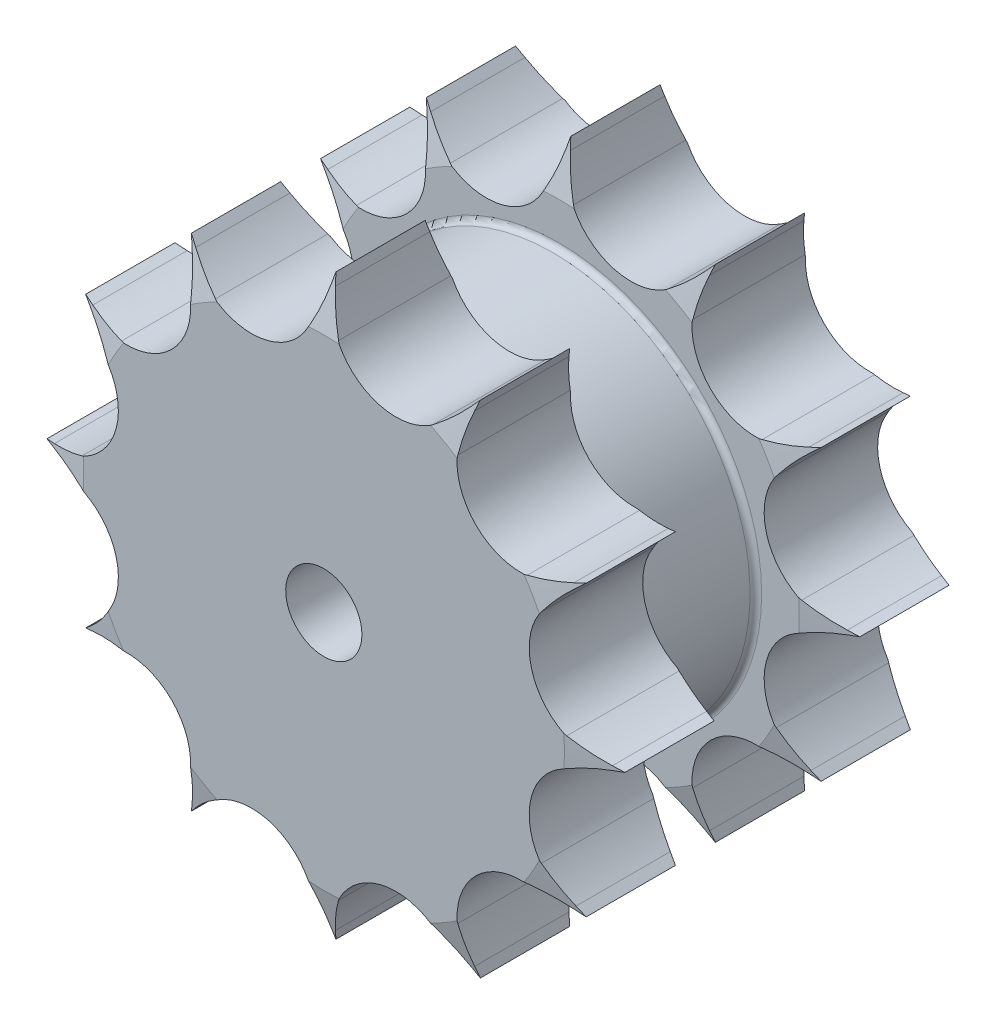
SolidWorks part; units mm, degrees
ref_plane "Front Plane" through (0, 0, 0) normal (0, 0, 1) x (1, 0, 0)
ref_plane "Top Plane" through (0, 0, 0) normal (0, 1, 0) x (1, 0, 0)
ref_plane "Right Plane" through (0, 0, 0) normal (1, 0, 0) x (0, 0, -1)
sketch "Sketch0" plane through (0, 0, 0) normal (0, 0, 1) x (1, 0, 0)
  line L0 (9, -33.5885) -> (0, 0) construction
  line L1 (0, 0) -> (24.5885, -24.5885) construction
  line L2 (0, 0) -> (-9, -33.5885) construction
  line L3 (9, -33.5885) -> (24.5885, -24.5885) construction
  line L4 (9, -33.5885) -> (-9, -33.5885) construction
  line L5 (18.2038, -31.414) -> (17.1631, -30.2446)
  line L6 (9, -33.5885) -> (0, -36) construction
  line L7 (-0.0579, -36.3072) -> (0.2586, -34.7741)
  line L8 (0, -33.5885) -> (0, -38.9885) construction
  line L9 (13.5764, -27.0527) -> (1.7156, -43.9917) construction
  line L10 (0, 0) -> (0, -33.5885) construction
  line L11 (17.1631, -30.2446) -> (1.7156, -43.9917) construction
  line L12 (0, -38.9885) -> (0, -36.0098) construction
  line L13 (28.2474, -22.476) -> (18.2038, -31.414) construction
  circle A0 centre (0, 0) radius 38.9885 construction
  circle A1 centre (0, 0) radius 34.7733 construction
  arc A2 (-18.1507, -46.0985) -> (38.7682, -30.8471) centre (0, 0) ccw
  circle A3 centre (0, 0) radius 36.0098 construction
  circle A4 centre (9, -33.5885) radius 7.9375 construction
  arc A7 (13.5764, -27.0527) -> (1.7689, -30.2165) centre (9, -33.5885) ccw
  circle A8 centre (9, -33.5885) radius 7.9787 construction
  arc A9 (18.2038, -31.414) -> (38.7682, -30.8471) centre (28.2474, -22.476) ccw
  arc A10 (17.1631, -30.2446) -> (13.5764, -27.0527) centre (1.7156, -43.9917) ccw
  arc A11 (-0.0579, -36.3072) -> (-18.1507, -46.0985) centre (-13.225, -33.5885) cw
  arc A12 (0.2586, -34.7741) -> (1.7689, -30.2165) centre (20.5101, -38.9557) cw
  dimension "D1" = 7.9787
  dimension "R" = 7.9787
sketch "Sketch1" plane through (0, 0, 0) normal (1, 0, 0) x (0, 0, -1)
  line L0 (7.0739, 0) -> (-7.0739, 0)
  line L1 (-7.0739, 25.2935) -> (-7.0739, 29.9885)
  line L2 (-7.0739, 29.9885) -> (-4.8239, 38.9885)
  line L3 (-4.8239, 38.9885) -> (4.8239, 38.9885)
  line L4 (4.8239, 38.9885) -> (7.0739, 29.9885)
  line L5 (7.0739, 29.9885) -> (7.0739, 0)
  line L6 (-22.2123, 25.2935) -> (-22.2123, 29.9885)
  line L7 (0, 38.9885) -> (0, 0) construction
  line L8 (-7.0739, 29.9885) -> (7.0739, 29.9885) construction
  line L9 (0, 38.9885) -> (0, -38.9885) construction
  line L10 (-7.0739, 29.9885) -> (-7.0739, 38.9885) construction
  line L11 (-7.0739, 38.9885) -> (-4.8239, 38.9885) construction
  line L12 (4.8239, 38.9885) -> (7.0739, 38.9885) construction
  line L13 (7.0739, 38.9885) -> (7.0739, 29.9885) construction
  line L14 (0, 0) -> (-29.2862, 0) construction
  line L15 (-14.6431, 0) -> (-14.6431, 38.9885) construction
  line L16 (7.0739, 38.9885) -> (-36.3601, 38.9885) construction
  line L17 (-36.3601, 0) -> (-22.2123, 0)
  line L18 (-36.3601, 29.9885) -> (-36.3601, 0)
  line L19 (-22.2123, 29.9885) -> (-24.4623, 38.9885)
  line L20 (-24.4623, 38.9885) -> (-34.1101, 38.9885)
  line L21 (-34.1101, 38.9885) -> (-36.3601, 29.9885)
  line L23 (-7.0739, 0) -> (-22.2123, 0)
  line L24 (-7.0739, 0) -> (-7.0739, 24.5735) construction
  line L25 (-36.3601, 38.9885) -> (-36.3601, 29.9885) construction
  line L26 (-34.1101, 38.9885) -> (-36.3601, 38.9885) construction
  line L27 (-22.2123, 29.9885) -> (-22.2123, 38.9885) construction
  line L28 (-22.2123, 38.9885) -> (-24.4623, 38.9885) construction
  line L29 (-7.7939, 24.5735) -> (-21.4923, 24.5735)
  line L30 (-29.2862, 0) -> (-29.2862, 38.9885) construction
  arc A0 (-7.7939, 24.5735) -> (-7.0739, 25.2935) centre (-7.7939, 25.2935) ccw
  arc A1 (-21.4923, 24.5735) -> (-22.2123, 25.2935) centre (-21.4923, 25.2935) cw
revolve "Revolve1" add sketch "Sketch1" angle 360 mid plane about L0
extrude "Cut-Extrude1" cut sketch "Sketch0" against normal through all and the other way through all
pattern_circular "CirPattern1" count 12 over 360 about axis through (0, 0, 0) along (0, 0, 1) of "Cut-Extrude1"
sketch "Sketch2" plane through (0, 0, 0) normal (0, 0, 1) x (1, 0, 0)
  circle A0 centre (0, 0) radius 9.525 construction
  circle A2 centre (0, 0) radius 54.991 construction
  dimension "Bore" = 19.05
  dimension "OD" = 109.982
sketch "Sketch3" plane through (0, 0, 36.3601) normal (0, 0, 1) x (1, 0, 0)
  circle A0 centre (0, 0) radius 4.75
  dimension "D1" = 9.5
extrude "Cut-Extrude2" cut sketch "Sketch3" against normal through all both and the other way through all contours A0
equation "\"360/N@Sketch0\" = 360/\"Teeth@CirPattern1\""
equation "\"Ds@Sketch0\" = 1.005 * \"Dr@Sketch0\" + 0.003"
equation "\"R@Sketch0\" = 1/2 * \"Ds@Sketch0\""
equation "\"A@Sketch0\" = 35 +  ( 60 / \"Teeth@CirPattern1\" ) "
equation "\"B@Sketch0\" = 18 -  ( 56 / \"Teeth@CirPattern1\" )"
equation "\"ac@Sketch0\" = 0.8 * \"Dr@Sketch0\""
equation "\"ab@Sketch0\" = 1.4 * \"Dr@Sketch0\""
equation "\"J@Sketch0\" = 0.3 * \"Pitch@Sketch0\""
equation "\"h@Sketch1\" = \"Pitch@Sketch0\" / 2"
equation "\"g@Sketch1\"= \"h@Sketch1\" / 4"
equation "\"MHD@Sketch1\" = \"Pitch@Sketch0\" * ( cotan ( 180 / \"Teeth@CirPattern1\" ) - 1 ) - 0.030"
equation "\"rf@Sketch1\" = 0.04 * \"Pitch@Sketch0\""
